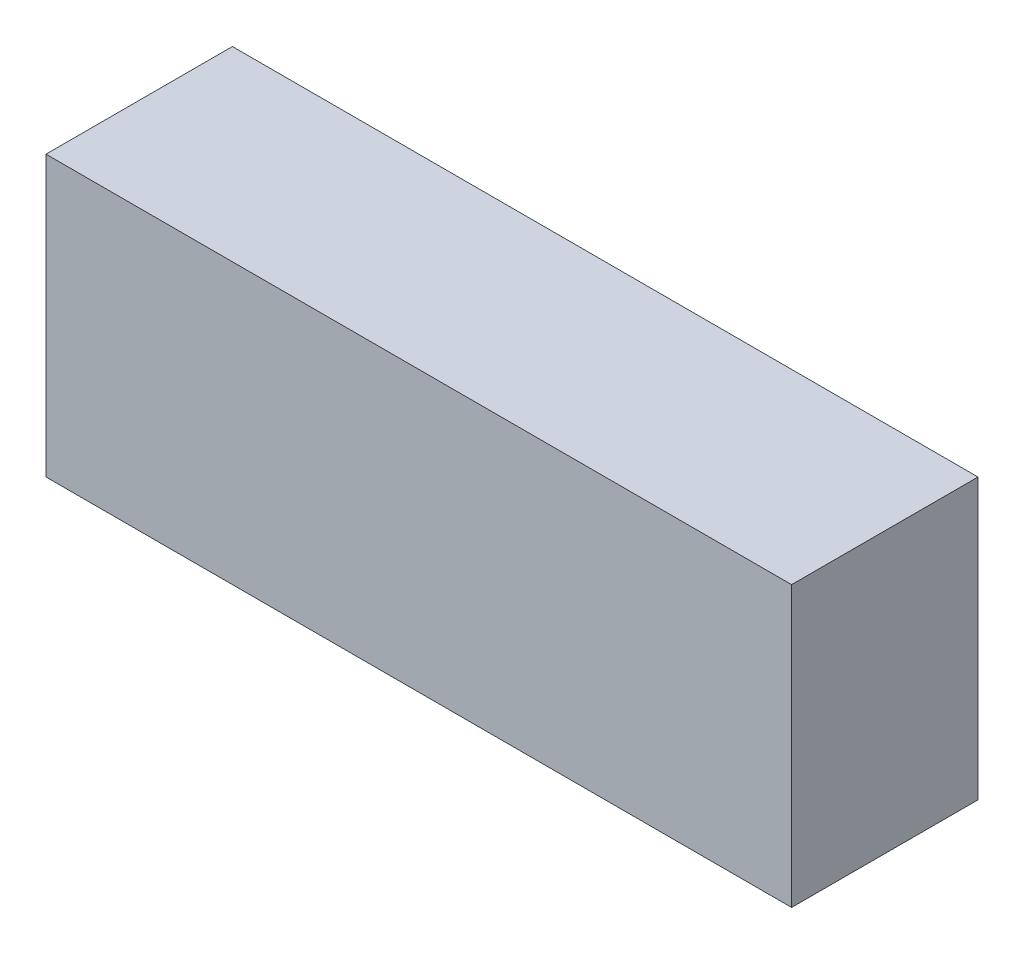
SolidWorks part; units mm, degrees
ref_plane "Front Plane" through (0, 0, 0) normal (0, 0, 1) x (1, 0, 0)
ref_plane "Top Plane" through (0, 0, 0) normal (0, 1, 0) x (1, 0, 0)
ref_plane "Right Plane" through (0, 0, 0) normal (1, 0, 0) x (0, 0, -1)
sketch "Sketch1" plane through (0, 0, 0) normal (0, 0, 1) x (1, 0, 0)
  line L1 (0, 0) -> (20.32, 0)
  line L2 (0, 0) -> (0, 7.62)
  line L3 (0, 7.62) -> (20.32, 7.62)
  line L4 (20.32, 0) -> (20.32, 7.62)
  dimension "D1" = 20.32
  dimension "D2" = 7.62
extrude "Boss-Extrude1" add sketch "Sketch1" along normal blind 5.08
equation "\"FoamCore\" = \".2\""
equation "\"MDF\" = \".2\""
equation "\"GMaterial\"= \".2\""
equation "\"PVCMountDiameter\" = \"0.5in\""
equation "\"PVCMountDistanceToEdge\" = \"0.5\""
equation "\"PVCThickness\" = \"0.13in\""
equation "\"PVCDiameter\" = 1.5in"
equation "\"BaseWidth\" = \"8in\""
equation "\"BaseLength\" = \"10in\""
equation "\"BallDiameter\" = \"38mm\""
equation "\"BaseGap\" = \"4in\""
equation "\"FunnelTopDiameter\" = \"8in\""
equation "\"FunnelTopDepth\" = \"0.5in\""
equation "\"BallGap\" = \"0.1in\""
equation "\"FunnelLength\" = 3in"
equation "\"FunnelMaterial\" = 0.1in"
equation "\"FunnelLowerDiameter\" = 1.9in"
equation "\"FunnelDepth\" = 1.5in"
equation "\"FunnelBendLength\" = 2*pi*\"FunnelLowerDiameter\"/2*135"
equation "\"AmmoFeederLength\" = 1.5in + 76mm"
equation "\"AmmoFeederCutoffLength\"= \"MovingWheelDiameter\""
equation "\"WheelThickness\" = 0.5in"
equation "\"LauncherWheelDiameter\" = 76mm"
equation "\"MotorFrontLength\" = 0.95in"
equation "\"MotorBodyTotalLength\" = 2.03in"
equation "\"MotorFrontDiameter\" = 1.5in"
equation "\"MotorLowerDriveshaftDiameter\" = 0.46in"
equation "\"MotorLowerDriveshaftThickness\" = 0.25in"
equation "\"MotorFullDriveshaftLength\" = 0.78in"
equation "\"MotorDriveshaftDiameter\" = 0.23in"
equation "\"MotorDriveshaftFlatThickness\" = 0.2in"
equation "\"MotorRearDiameter\" = 31.9mm"
equation "\"MotorDriveshaftBottomToTop\" = 31.1mm"
equation "\"MotorFlatDriveshaftLength\" = 11.7mm"
equation "\"MotorDistanceBetweenLowerandTopHoles\" = 0.5in"
equation "\"MotorMountsDistanceFromEdge\" = 0.06in"
equation "\"MotorScrewMountDiameter\" = 0.1in"
equation "\"MotorScrewMountDepth\" = 0.13in"
equation "\"HBRidgeScrewHoleDeep\" = 0.18in"
equation "\"MotorMountWidth\" = \"1.61in\""
equation "\"MotorMountLength\" = \"1.58in\""
equation "\"MotorMountToEdgeGap\" = \"3.3mm\""
equation "\"MotorMountToInsideEdgeGap\" = \"6.5mm\""
equation "\"MotorMountToMountWidthGap\" = \"25.8mm\""
equation "\"MotorMountToMountLengthGap\" = \"20.5mm\""
equation "\"MotorMountMaterialThickness\" = 1.6mm"
equation "\"MotorMountBaseScrewholeDiameter\" = 3.8mm"
equation "\"MotorMountBaseDistancebetweenHoles\" = 0.8in"
equation "\"MotorMountHeight\" = 1.85in"
equation "\"HBridgeWidth\" = 2.25in"
equation "\"HBridgeLength\" = 1.40in"
equation "\"UnoWidth\" = 3.13in"
equation "\"UnoLength\" = 3.06in"
equation "\"BatteryWidth\" = 1.15in"
equation "\"BatteryLength\" = 3.86in"
equation "\"ScrewDiameter\" = 2.7mm"
equation "\"MotorMountFaceScrewtoBase\" = 0.46in"
equation "\"MotorMountFaceDistanceBetweenScrews\" = 0.95in"
equation "\"MotorMountFaceMiddletoEdge\" = 0.16in"
equation "\"MotorMountFaceBottomtoEdge\" = 0.42in"
equation "\"MotorMountCenterholeHeight\" = 1.04in"
equation "\"MotorMountCenterholetoEdge\" = 0.25in"
equation "\"MovingWheelDiameter\" = 76mm"
equation "\"MovingWheelThickness\" = 0.5in"
equation "\"BraceLength\" = 1in"
equation "\"BraceVerticalOffset\" = 3.5in"
equation "\"BraceHorizontalOffset\" = 2.5in"
equation "\"BaseToBaseDistance\" = 3in"
equation "\"PVCOutsideDiameter\" = \"PVCDiameter\" + 2*\"PVCThickness\""
equation "\"Distancebetweenwalls\" = 6in"
equation "\"Slidewidth\" = 0.3in"
equation "\"Slidelength\" = 0.8in"
equation "\"D1@Sketch1\"=\"Slidelength\""
equation "\"D2@Sketch1\"=\"Slidewidth\""
equation "\"D1@Boss-Extrude1\"=\"MDF\""
